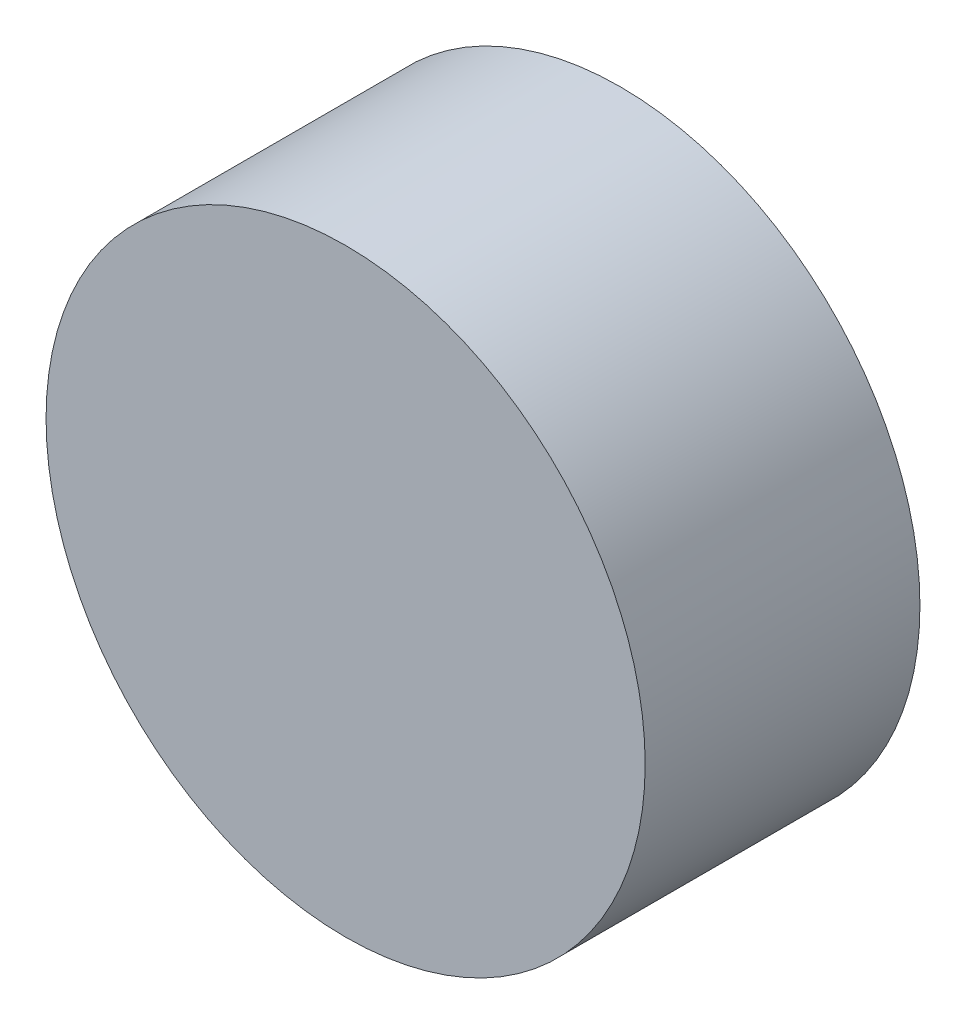
SolidWorks part; units mm, degrees
ref_plane "Front Plane" through (0, 0, 0) normal (0, 0, 1) x (1, 0, 0)
ref_plane "Top Plane" through (0, 0, 0) normal (0, 1, 0) x (1, 0, 0)
ref_plane "Right Plane" through (0, 0, 0) normal (1, 0, 0) x (0, 0, -1)
sketch "Sketch1" plane through (0, 0, 0) normal (0, 0, 1) x (1, 0, 0)
  circle A0 centre (0, 0) radius 7.366
  dimension "D1" = 14.732
extrude "Boss-Extrude1" add sketch "Sketch1" along normal blind 6.7564
